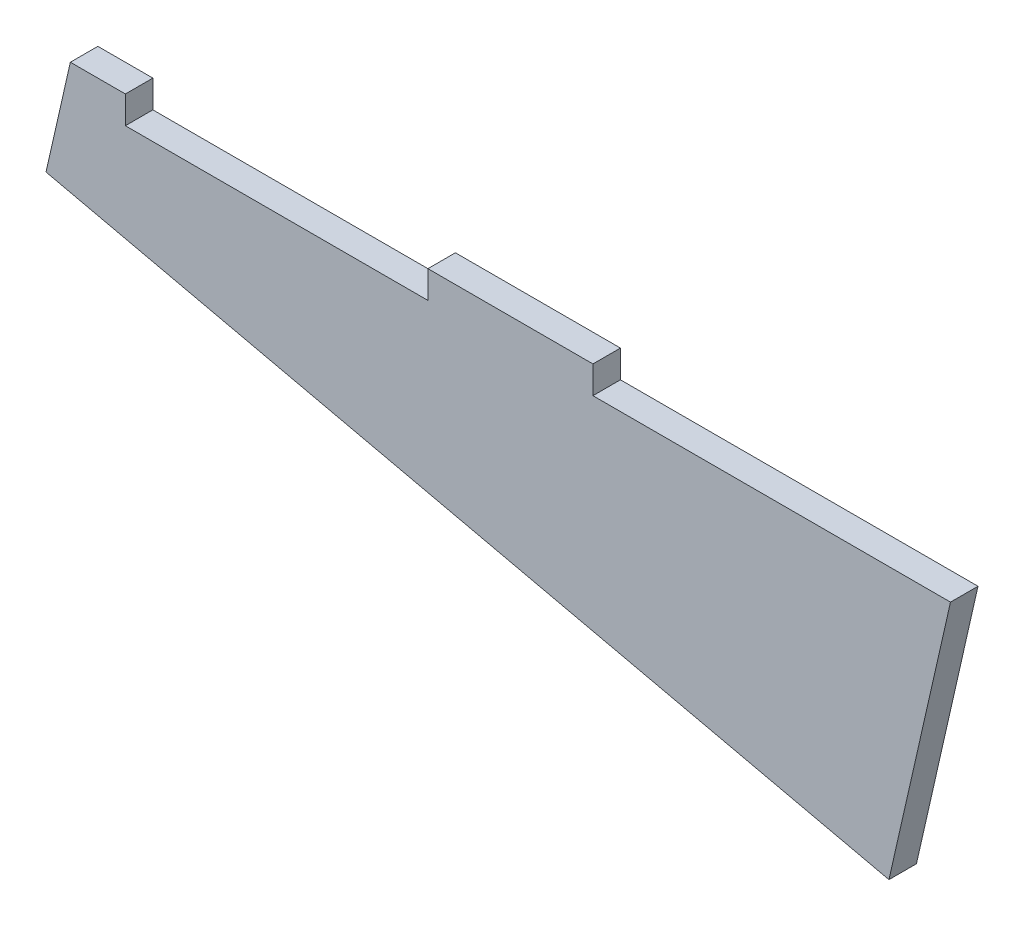
SolidWorks part; units mm, degrees
ref_plane "Front Plane" through (0, 0, 0) normal (0, 0, 1) x (1, 0, 0)
ref_plane "Top Plane" through (0, 0, 0) normal (0, 1, 0) x (1, 0, 0)
ref_plane "Right Plane" through (0, 0, 0) normal (1, 0, 0) x (0, 0, -1)
sketch "Sketch1" plane through (0, 0, 0) normal (0, 0, 1) x (1, 0, 0)
  line L0 (-186.4515, -43.5946) -> (-173.7515, -43.5946)
  line L4 (-173.7515, -43.5946) -> (-173.7515, -49.9446)
  line L5 (-173.7515, -49.9446) -> (-103.9015, -49.9446)
  line L6 (-103.9015, -49.9446) -> (-103.9015, -43.5946)
  line L7 (-103.9015, -43.5946) -> (-65.8015, -43.5946)
  line L8 (-65.8015, -43.5946) -> (-65.8015, -49.9446)
  line L9 (-65.8015, -49.9446) -> (16.7485, -49.9446)
  line L10 (16.7485, -49.9446) -> (2.5379, -112.5435)
  line L11 (2.5379, -112.5435) -> (-192.0745, -68.3643)
  line L12 (-192.0745, -68.3643) -> (-186.4515, -43.5946)
  line L13 (-1521.6894, 245.3765) -> (-1127.9894, 156.0023) construction
  point P2 (-62.7286, -30.0583)
  dimension "D1" = 12.7
  dimension "D2" = 6.35
  dimension "D3" = 69.85
  dimension "D4" = 38.1
  dimension "D5" = 82.55
  dimension "D6" = 25.4
extrude "Boss-Extrude1" add sketch "Sketch1" against normal blind 6.35
